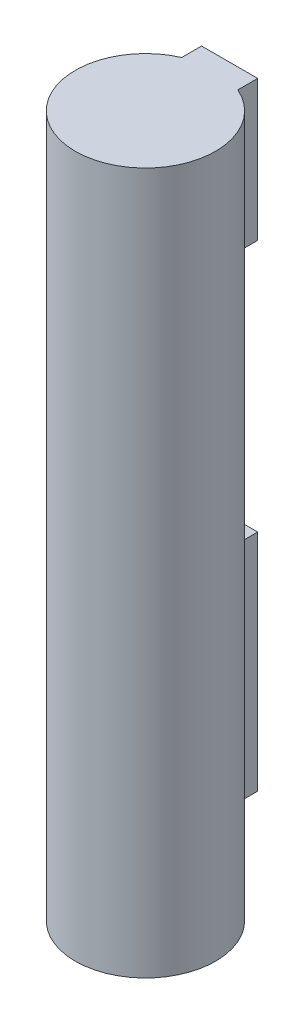
SolidWorks part; units mm, degrees
ref_plane "前视基准面" through (0, 0, 0) normal (0, 0, 1) x (1, 0, 0)
ref_plane "上视基准面" through (0, 0, 0) normal (0, 1, 0) x (1, 0, 0)
ref_plane "右视基准面" through (0, 0, 0) normal (1, 0, 0) x (0, 0, -1)
other "Configuration Table"
sketch "草图1" plane through (0, 0, 0) normal (0, 1, 0) x (1, 0, 0)
  circle A0 centre (0, 0) radius 2.5
  dimension "D1" = 5
extrude "凸台-拉伸1" add sketch "草图1" along normal blind 25
ref_plane "基准面1" through (0, 3, 0) normal (0, -1, 0) x (-1, 0, 0)
sketch "草图2" plane through (0, 3, 0) normal (0, -1, 0) x (-1, 0, 0)
  line L1 (-1, 3) -> (1, 3)
  line L2 (-1, 3) -> (-1, 2)
  line L3 (-1, 2) -> (1, 2)
  line L4 (1, 3) -> (1, 2)
  line L5 (-1, 3) -> (1, 2) construction
  line L6 (-1, 2) -> (1, 3) construction
  circle A0 centre (0, 0) radius 2.5 construction
  point P0 (0, 2.5)
  dimension "D1" = 2
  dimension "D2" = 1
extrude "凸台-拉伸2" add sketch "草图2" against normal blind 8
sketch "草图3" plane through (0, 25, 0) normal (0, 1, 0) x (1, 0, 0)
  line L6 (-1, 3) -> (-1, 2.2913)
  line L7 (1, 2.2913) -> (1, 3)
  line L8 (1, 3) -> (-1, 3)
  line L9 (-1, 3) -> (-1, 2.2913)
  line L10 (1, 2.2913) -> (1, 3)
  line L11 (1, 3) -> (-1, 3)
  arc A2 (1, 2.2913) -> (-1, 2.2913) centre (0, 0) ccw
  arc A3 (1, 2.2913) -> (-1, 2.2913) centre (0, 0) ccw
  dimension "D1" = 0
extrude "凸台-拉伸3" add sketch "草图3" against normal blind 5
